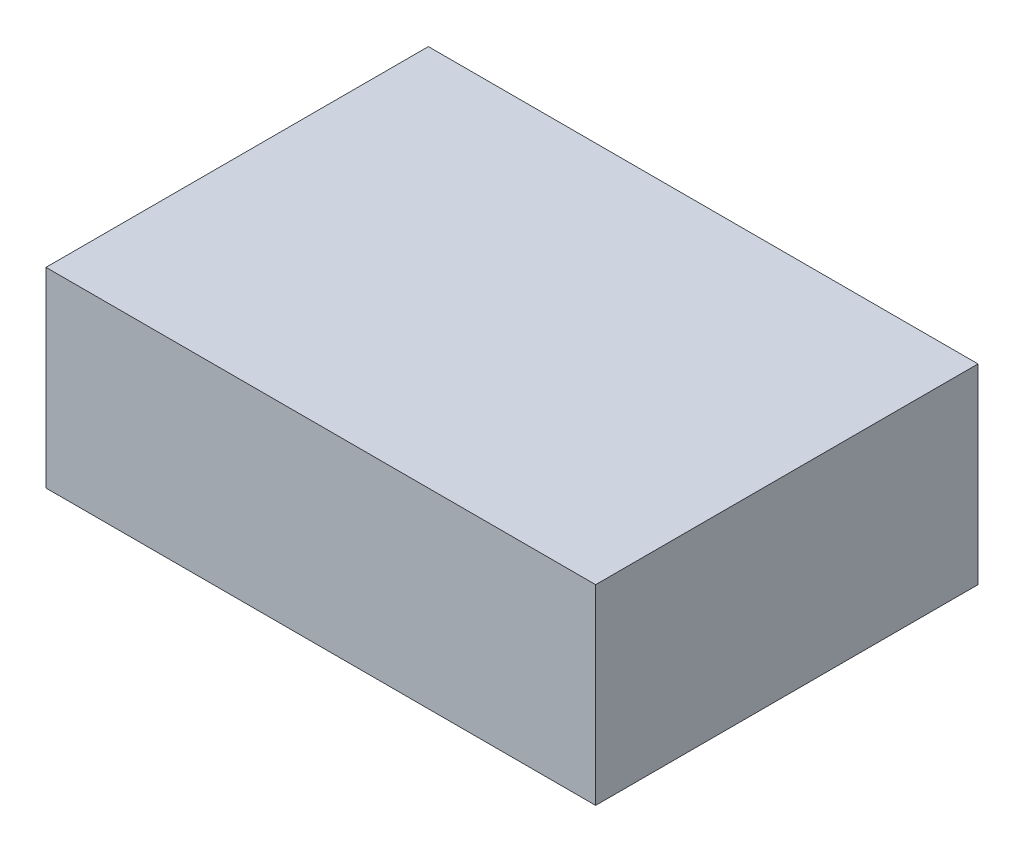
SolidWorks part; units mm, degrees
ref_plane "Front Plane" through (0, 0, 0) normal (0, 0, 1) x (1, 0, 0)
ref_plane "Top Plane" through (0, 0, 0) normal (0, 1, 0) x (1, 0, 0)
ref_plane "Right Plane" through (0, 0, 0) normal (1, 0, 0) x (0, 0, -1)
sketch "Sketch2" plane through (0, 0, 0) normal (0, 1, 0) x (1, 0, 0)
  line L7 (0, 0) -> (292.1, 0)
  line L8 (0, 0) -> (0, 203.2)
  line L9 (0, 203.2) -> (292.1, 203.2)
  line L10 (292.1, 0) -> (292.1, 203.2)
  dimension "D1" = 203.2
  dimension "D2" = 292.1
extrude "Boss-Extrude1" add sketch "Sketch2" along normal blind 12.7
sketch "Sketch3" plane through (0, 0, 0) normal (0, -1, 0) x (1, 0, 0)
  line L0 (12.7, -12.7) -> (12.7, -190.5)
  line L1 (12.7, -190.5) -> (279.4, -190.5)
  line L2 (279.4, -190.5) -> (279.4, -12.7)
  line L3 (279.4, -12.7) -> (12.7, -12.7)
  line L4 (0, 0) -> (0, -203.2)
  line L5 (0, -203.2) -> (292.1, -203.2)
  line L6 (292.1, -203.2) -> (292.1, 0)
  line L7 (292.1, 0) -> (0, 0)
  line L8 (0, 0) -> (0, -203.2)
  line L9 (0, -203.2) -> (292.1, -203.2)
  line L10 (292.1, -203.2) -> (292.1, 0)
  line L11 (292.1, 0) -> (0, 0)
  dimension "D1" = 0
  dimension "D2" = 12.7
extrude "Boss-Extrude2" add sketch "Sketch3" along normal blind 88.9
sketch "Sketch4" plane through (0, 0, 0) normal (-1, 0, 0) x (0, 0, 1)
  line L0 (0, -88.9) -> (-203.2, -88.9) construction
  line L1 (-25.4, -88.9) -> (-177.8, -88.9)
  line L2 (-25.4, -88.9) -> (-25.4, -25.4)
  line L3 (-25.4, -25.4) -> (-177.8, -25.4)
  line L4 (-177.8, -88.9) -> (-177.8, -25.4)
  line L5 (0, 12.7) -> (0, -88.9) construction
  line L6 (-203.2, 12.7) -> (-203.2, -88.9) construction
  line L7 (-203.2, 12.7) -> (0, 12.7) construction
  point P8 (-177.8, -57.15)
  dimension "D1" = 25.4
  dimension "D2" = 25.4
  dimension "D3" = 38.1
extrude "Cut-Extrude1" cut sketch "Sketch4" against normal up to next
